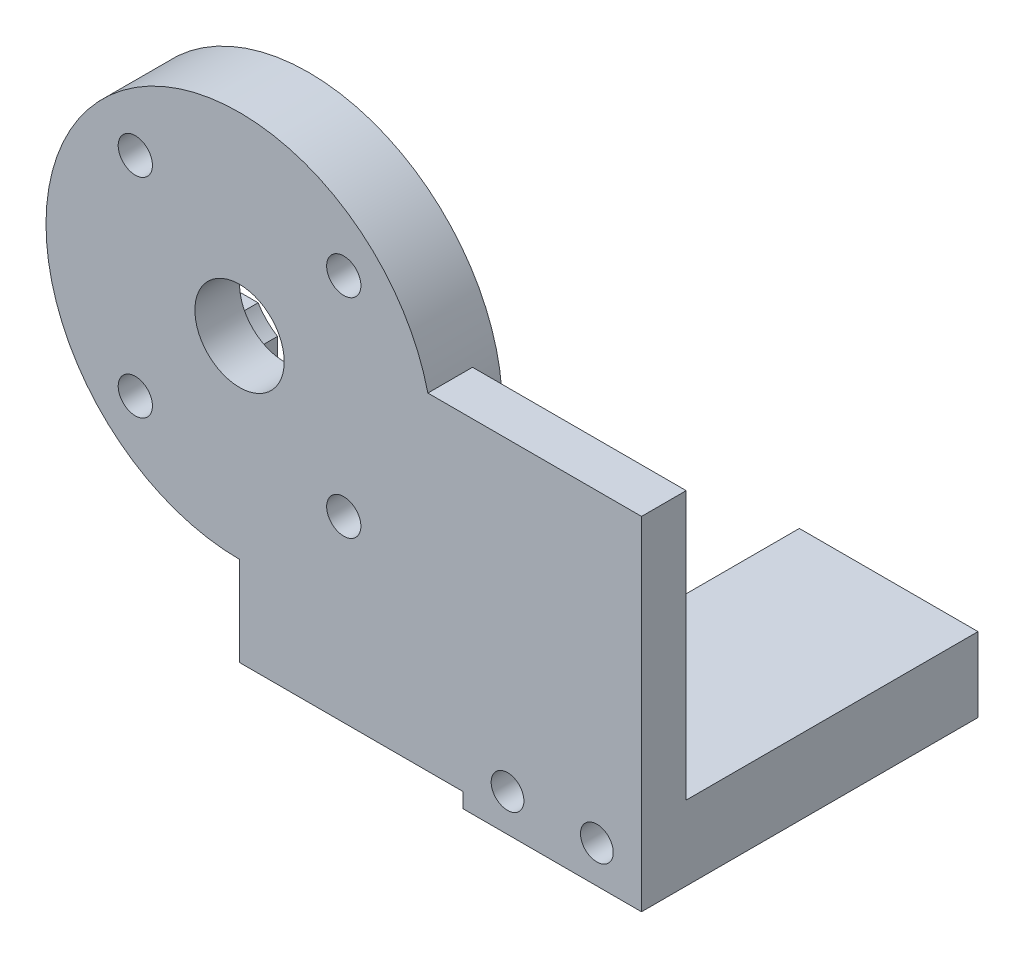
SolidWorks part; units mm, degrees
ref_plane "Front Plane" through (0, 0, 0) normal (0, 0, 1) x (1, 0, 0)
ref_plane "Top Plane" through (0, 0, 0) normal (0, 1, 0) x (1, 0, 0)
ref_plane "Right Plane" through (0, 0, 0) normal (1, 0, 0) x (0, 0, -1)
sketch "Stock_horn_attachment_profile" plane through (0, 0, 0) normal (0, 0, 1) x (1, 0, 0)
  circle A0 centre (0, 0) radius 13
  dimension "D1" = 26
extrude "Stock_horn_attachment" add sketch "Stock_horn_attachment_profile" along normal blind 3 from offset 19.6
sketch "Finger_arm_profile" plane through (0, 0, 0) normal (0, 0, 1) x (1, 0, 0)
  line L1 (0, -19) -> (27, -19)
  line L2 (0, -19) -> (0, 3)
  line L3 (0, 3) -> (27, 3)
  line L4 (27, -19) -> (27, 3)
  dimension "D1" = 27
  dimension "D2" = 22
extrude "Finger_arm" add sketch "Finger_arm_profile" along normal blind 3 from offset 19.6
sketch "Descending_contact_finger_profile" plane through (0, 0, 0) normal (0, 0, 1) x (1, 0, 0)
  line L1 (15, -20) -> (27, -20)
  line L2 (15, -20) -> (15, -15)
  line L3 (15, -15) -> (27, -15)
  line L4 (27, -20) -> (27, -15)
  dimension "D1" = 12
  dimension "D2" = 5
extrude "Descending_contact_finger" add sketch "Descending_contact_finger_profile" along normal blind 22.6
sketch "Horn_center_access_profile" plane through (0, 0, 0) normal (0, 0, 1) x (1, 0, 0)
  circle A0 centre (0, 0) radius 3
  dimension "D1" = 6
extrude "Horn_center_access" cut sketch "Horn_center_access_profile" along normal through all from offset 50
sketch "Captured_horn_key_boss_profile" plane through (0, 0, 0) normal (0, 0, 1) x (1, 0, 0)
  circle A0 centre (0, 0) radius 13
  dimension "D1" = 26
extrude "Captured_horn_key_boss" add sketch "Captured_horn_key_boss_profile" along normal blind 1.65 from offset 17.95
sketch "Stock_horn_pocket_Hub" plane through (0, 0, 0) normal (0, 0, 1) x (1, 0, 0)
  circle A0 centre (0, 0) radius 3.55
  dimension "D1" = 7.1
extrude "Key_pocket_Hub" cut sketch "Stock_horn_pocket_Hub" along normal blind 1.65 from offset 17.95
sketch "Stock_horn_pocket_Horizontal" plane through (0, 0, 0) normal (0, 0, 1) x (1, 0, 0)
  line L1 (-8.15, -2.1) -> (8.15, -2.1)
  line L2 (-8.15, -2.1) -> (-8.15, 2.1)
  line L3 (-8.15, 2.1) -> (8.15, 2.1)
  line L4 (8.15, -2.1) -> (8.15, 2.1)
  dimension "D1" = 16.3
  dimension "D2" = 4.2
extrude "Key_pocket_Horizontal" cut sketch "Stock_horn_pocket_Horizontal" along normal blind 1.65 from offset 17.95
sketch "Stock_horn_pocket_Vertical" plane through (0, 0, 0) normal (0, 0, 1) x (1, 0, 0)
  line L1 (-2.1, -8.15) -> (2.1, -8.15)
  line L2 (-2.1, -8.15) -> (-2.1, 8.15)
  line L3 (-2.1, 8.15) -> (2.1, 8.15)
  line L4 (2.1, -8.15) -> (2.1, 8.15)
  dimension "D1" = 4.2
  dimension "D2" = 16.3
extrude "Key_pocket_Vertical" cut sketch "Stock_horn_pocket_Vertical" along normal blind 1.65 from offset 17.95
sketch "Stock_horn_pocket_Rounded_tips" plane through (0, 0, 0) normal (0, 0, 1) x (1, 0, 0)
  circle A0 centre (8.15, 0) radius 2.1
  circle A1 centre (-8.15, 0) radius 2.1
  circle A2 centre (0, 8.15) radius 2.1
  circle A3 centre (0, -8.15) radius 2.1
  dimension "D1" = 4.2
  dimension "D2" = 4.2
  dimension "D3" = 4.2
  dimension "D4" = 4.2
extrude "Key_pocket_Rounded_tips" cut sketch "Stock_horn_pocket_Rounded_tips" along normal blind 1.65 from offset 17.95
sketch "Unmodified_horn_capture_M2_profile" plane through (0, 0, 0) normal (0, 0, 1) x (1, 0, 0)
  circle A0 centre (7, 7) radius 1.15
  circle A1 centre (-7, 7) radius 1.15
  circle A2 centre (-7, -7) radius 1.15
  circle A3 centre (7, -7) radius 1.15
  dimension "D1" = 2.3
  dimension "D2" = 2.3
  dimension "D3" = 2.3
  dimension "D4" = 2.3
extrude "Unmodified_horn_capture_M2" cut sketch "Unmodified_horn_capture_M2_profile" along normal through all from offset 50
sketch "Horn_center_hub_clearance" plane through (0, 0, 0) normal (0, 0, 1) x (1, 0, 0)
  circle A0 centre (0, 0) radius 4
  dimension "D1" = 8
extrude "Hub_clearance_in_key_boss_only" cut sketch "Horn_center_hub_clearance" along normal blind 1.65 from offset 17.95
sketch "Contact_pad_keeper_profile" plane through (0, 0, 0) normal (0, 0, 1) x (1, 0, 0)
  circle A0 centre (18, -17.5) radius 1.1
  circle A1 centre (24, -17.5) radius 1.1
  dimension "D1" = 2.2
  dimension "D2" = 2.2
extrude "Contact_pad_keeper" cut sketch "Contact_pad_keeper_profile" along normal through all from offset 50
